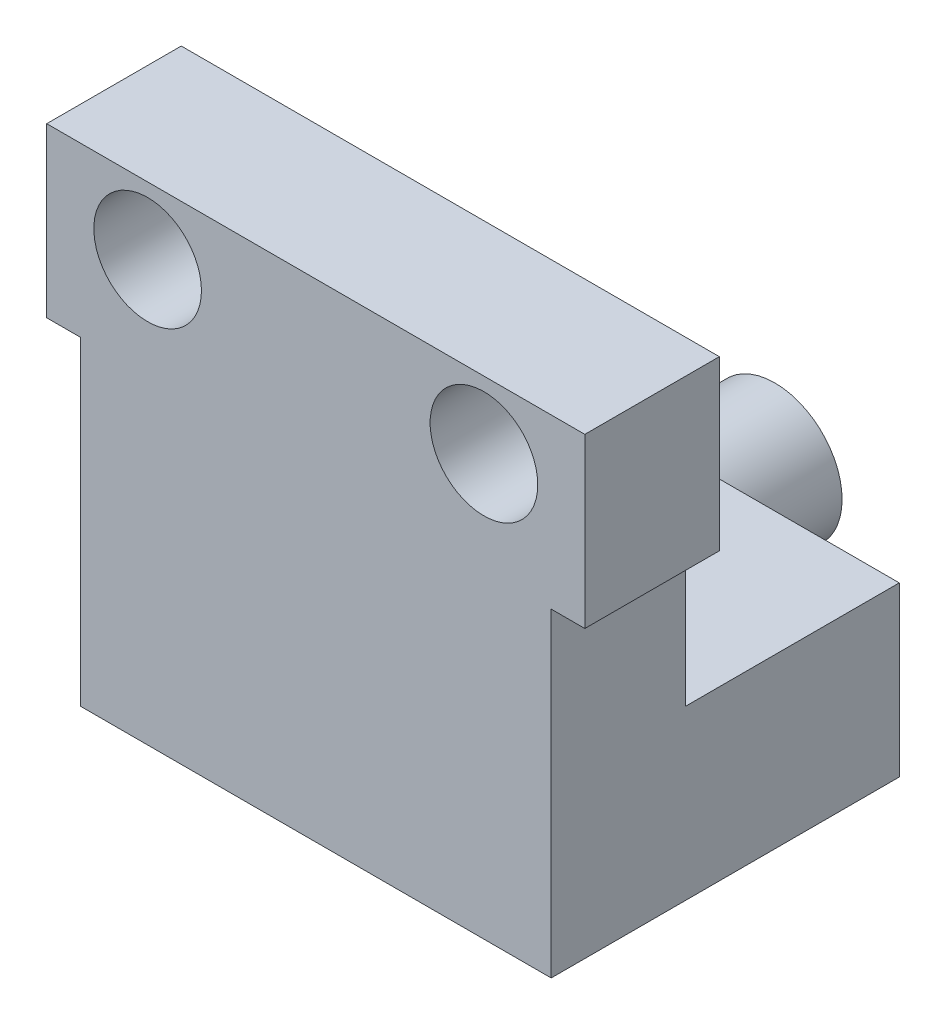
SolidWorks part; units mm, degrees
ref_plane "前视基准面" through (0, 0, 0) normal (0, 0, 1) x (1, 0, 0)
ref_plane "上视基准面" through (0, 0, 0) normal (0, 1, 0) x (1, 0, 0)
ref_plane "右视基准面" through (0, 0, 0) normal (1, 0, 0) x (0, 0, -1)
other "Configuration Table"
sketch "Integrated horizontal stop pad profile" plane through (0, 0, 0) normal (0, 0, 1) x (1, 0, 0)
  line L0 (-8, 24) -> (8, 24)
  line L1 (8, 24) -> (8, 29)
  line L2 (8, 29) -> (-8, 29)
  line L3 (-8, 29) -> (-8, 24)
extrude "Integrated horizontal stop pad" add sketch "Integrated horizontal stop pad profile" along normal blind 4 from offset 53
sketch "Integral upright profile" plane through (0, 0, 0) normal (0, 0, 1) x (1, 0, 0)
  line L0 (-7, 14.5) -> (7, 14.5)
  line L1 (7, 14.5) -> (7, 24.2)
  line L2 (7, 24.2) -> (-7, 24.2)
  line L3 (-7, 24.2) -> (-7, 14.5)
extrude "Integral upright" add sketch "Integral upright profile" along normal blind 4 from offset 53
sketch "Horizontal limit pin arm profile" plane through (0, 0, 0) normal (0, 0, 1) x (1, 0, 0)
  line L0 (-7, 14.5) -> (7, 14.5)
  line L1 (7, 14.5) -> (7, 19.5)
  line L2 (7, 19.5) -> (-7, 19.5)
  line L3 (-7, 19.5) -> (-7, 14.5)
extrude "Horizontal limit pin arm" add sketch "Horizontal limit pin arm profile" along normal blind 6.55 from offset 46.65
sketch "Built in stop pin diameter 4 mm profile" plane through (0, 0, 0) normal (0, 0, 1) x (1, 0, 0)
  circle A0 centre (0, 17.5) radius 2
  point P2 (-7, 14)
  dimension "D3" = 4
  dimension "D1" = 7
  dimension "D2" = 3.5
extrude "Built in stop pin diameter 4 mm" add sketch "Built in stop pin diameter 4 mm profile" along normal blind 3.5 from offset 43.35
sketch "Stop clearance two M3 holes 10 mm pitch profile" plane through (0, 0, 0) normal (0, 0, 1) x (1, 0, 0)
  circle A0 centre (-5, 27) radius 1.6
  circle A1 centre (5, 27) radius 1.6
  point P4 (-8, 24)
  dimension "D3" = 3.2
  dimension "D6" = 3.2
  dimension "D1" = 3
  dimension "D2" = 3
  dimension "D4" = 13
  dimension "D5" = 3
extrude "Stop clearance two M3 holes 10 mm pitch" cut sketch "Stop clearance two M3 holes 10 mm pitch profile" along normal blind 4.2 from offset 52.9
